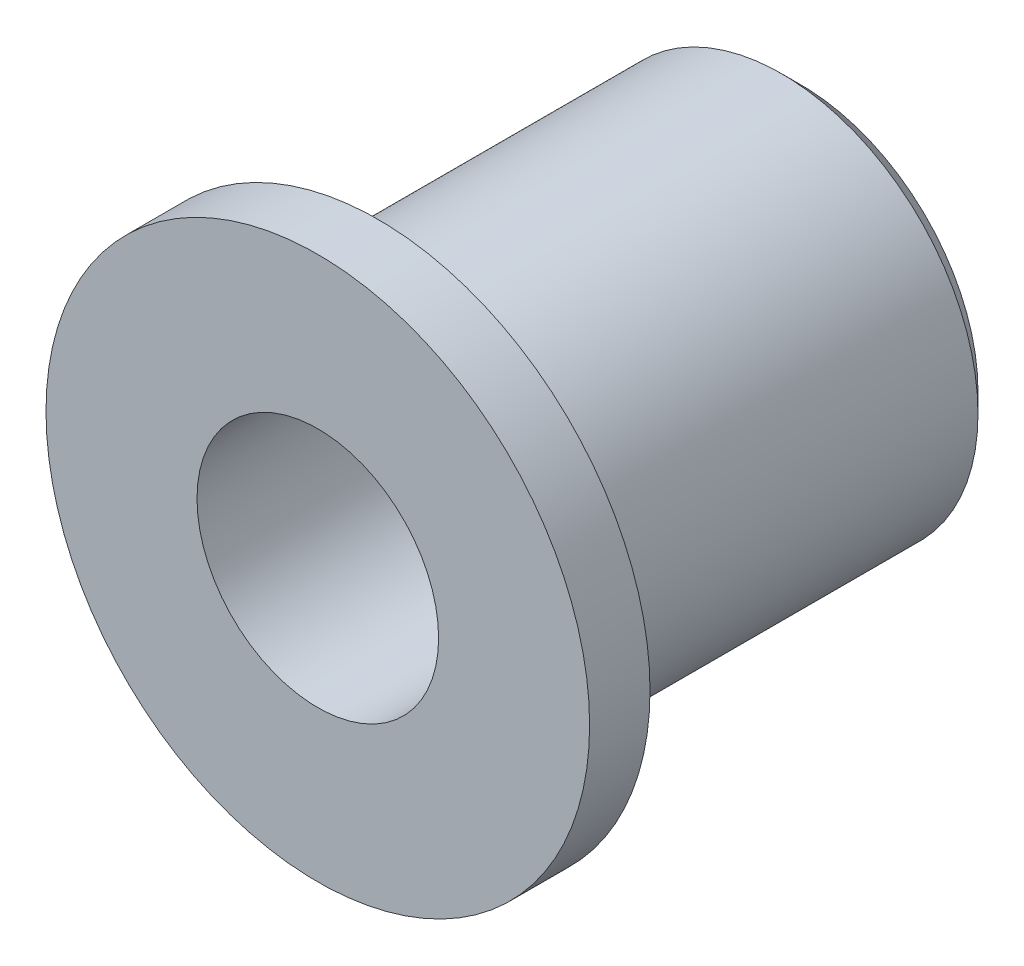
SolidWorks part; units mm, degrees
ref_plane "Front" through (0, 0, 0) normal (0, 0, 1) x (1, 0, 0)
ref_plane "Top" through (0, 0, 0) normal (0, 1, 0) x (1, 0, 0)
ref_plane "Right" through (0, 0, 0) normal (1, 0, 0) x (0, 0, -1)
sketch "Sketch1" plane through (0, 0, 0) normal (1, 0, 0) x (0, 0, -1)
  line L0 (0, 0) -> (0, 7.1438)
  line L1 (0, 7.1438) -> (1.5875, 7.1437)
  line L2 (1.5875, 7.1437) -> (1.5875, 5.0562) construction
  line L3 (1.8971, 5.0562) -> (1.4843, 5.0562)
  line L4 (1.8971, 5.0562) -> (1.8971, 5.1594)
  line L5 (1.8971, 5.1594) -> (12.7, 5.1594)
  line L6 (12.7, 5.1594) -> (12.7, 0)
  line L7 (12.7, 0) -> (0, 0)
  line L8 (0, 0) -> (-27.4679, 0) construction
  line L9 (1.4843, 5.0562) -> (1.4843, 5.4689)
  line L10 (1.4843, 5.4689) -> (1.5875, 5.4689)
  line L11 (1.5875, 5.4689) -> (1.5875, 7.1437)
  dimension "L" = 14.2875
  dimension "J" = 10.3187
  dimension "K" = 11.1125
  dimension "D4" = 1.5875
  dimension "D5" = 0.1032
  dimension "D1" = 0.4127
revolve "Revolve1" add sketch "Sketch1" angle 360 about L8
sketch "Sketch2" plane through (0, 0, 0) normal (0, 0, 1) x (1, 0, 0)
  circle A0 centre (0, 0) radius 3.175
  dimension "D1" = 6.35
extrude "Cut-Extrude1" cut sketch "Sketch2" against normal through all
chamfer "Chamfer1" distance 0.508 angle 45 1 edges at (-5.1594, 0, -12.7)
equation "\"D5@Sketch1\" = \"J@Sketch1\"*.01"
equation "\"D1@Sketch1\" = \"D5@Sketch1\"*4"
